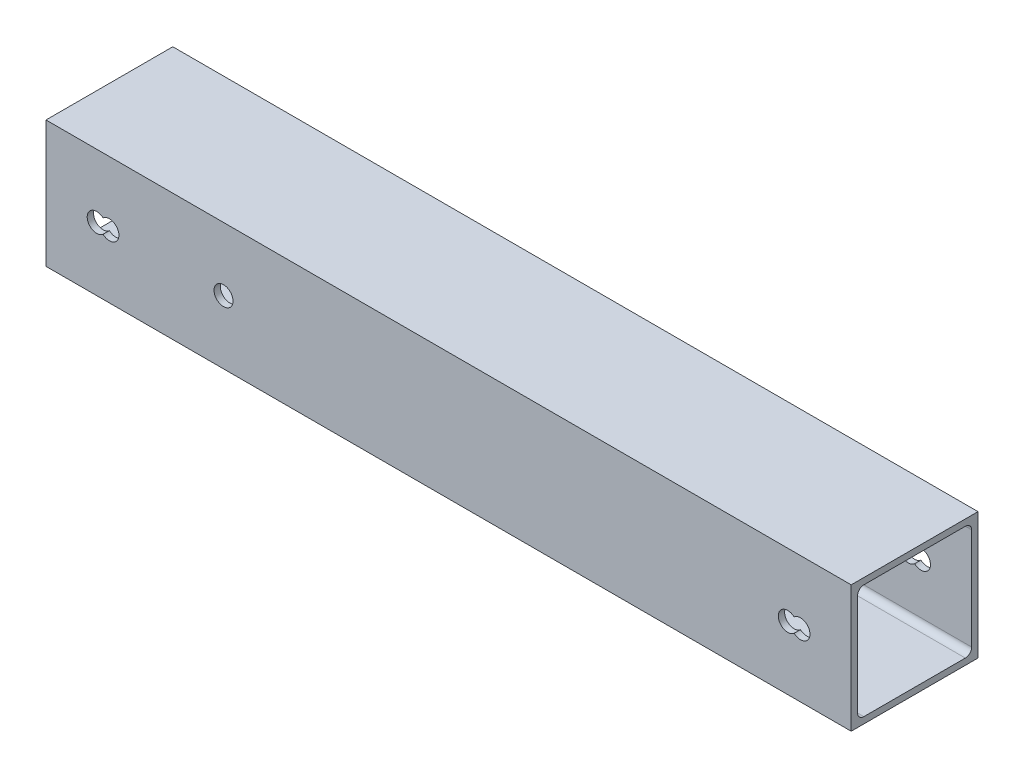
SolidWorks part; units mm, degrees
material "Thornel Mat VMA"
ref_plane "Front Plane" through (0, 0, 0) normal (0, 0, 1) x (1, 0, 0)
ref_plane "Top Plane" through (0, 0, 0) normal (0, 1, 0) x (1, 0, 0)
ref_plane "Right Plane" through (0, 0, 0) normal (1, 0, 0) x (0, 0, -1)
sketch "Sketch1" plane through (0, 0, 0) normal (1, 0, 0) x (0, 0, -1)
  line L1 (-8, -9) -> (8, -9)
  line L2 (-9, -8) -> (-9, 8)
  line L3 (-8, 9) -> (8, 9)
  line L4 (9, -8) -> (9, 8)
  line L5 (-9, -9) -> (9, 9) construction
  line L6 (-9, 9) -> (9, -9) construction
  line L7 (-10, -10) -> (10, -10)
  line L8 (-10, -10) -> (-10, 10)
  line L9 (-10, 10) -> (10, 10)
  line L10 (10, -10) -> (10, 10)
  line L11 (-10, -10) -> (10, 10) construction
  line L12 (-10, 10) -> (10, -10) construction
  arc A0 (-8, -9) -> (-9, -8) centre (-8, -8) cw
  arc A1 (8, -9) -> (9, -8) centre (8, -8) ccw
  arc A2 (8, 9) -> (9, 8) centre (8, 8) cw
  arc A3 (-9, 8) -> (-8, 9) centre (-8, 8) cw
  point P0 (0, 0)
  point P6 (0, 0)
  dimension "D5" = 1
  dimension "D1" = 20
  dimension "D2" = 20
  dimension "D3" = 1
  dimension "D4" = 1
extrude "Boss-Extrude1" add sketch "Sketch1" along normal blind 127
sketch "Sketch5" plane through (0, 0, 10) normal (0, 0, 1) x (1, 0, 0)
  line L0 (0, 10) -> (0, -10) construction
  line L1 (127, 10) -> (127, -10) construction
  circle A0 centre (10, 0) radius 1.5
  circle A1 centre (117, 0) radius 1.5
  dimension "D1" = 3
  dimension "D2" = 3
  dimension "D3" = 10
  dimension "D4" = 10
extrude "Cut-Extrude4" cut sketch "Sketch5" against normal blind 20
sketch "Sketch2" plane through (0, 0, 10) normal (0, 0, 1) x (1, 0, 0)
  line L0 (0, 10) -> (0, -10) construction
  circle A0 centre (8, 0) radius 1.5
  circle A1 centre (28, 0) radius 1.5
  dimension "D1" = 3
  dimension "D2" = 3
  dimension "D3" = 20
  dimension "D4" = 8
extrude "Cut-Extrude1" cut sketch "Sketch2" against normal blind 600
sketch "Sketch3" plane through (0, 0, 10) normal (0, 0, 1) x (1, 0, 0)
  line L0 (127, 10) -> (127, -10) construction
  circle A0 centre (119, 0) radius 1.5
  circle A1 centre (139, 0) radius 1.5
  dimension "D1" = 20
  dimension "D2" = 8
  dimension "D3" = 3
  dimension "D4" = 3
extrude "Cut-Extrude2" cut sketch "Sketch3" against normal blind 30
